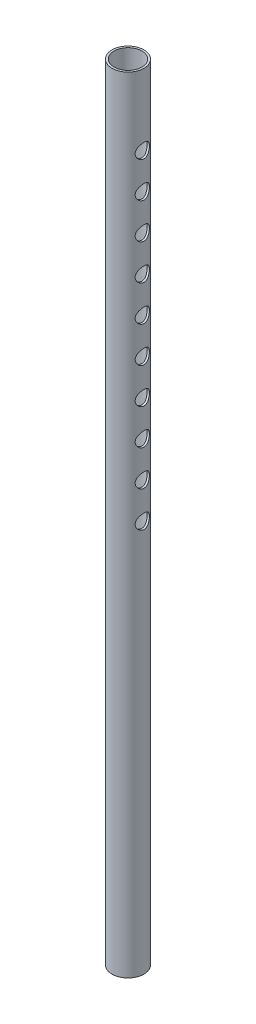
SolidWorks part; units mm, degrees
material "1060 Alloy"
ref_plane "Спереди" through (0, 0, 0) normal (0, 0, 1) x (1, 0, 0)
ref_plane "Сверху" through (0, 0, 0) normal (0, 1, 0) x (1, 0, 0)
ref_plane "Справа" through (0, 0, 0) normal (1, 0, 0) x (0, 0, -1)
sketch "Эскиз1" plane through (0, 0, 0) normal (0, 0, 1) x (1, 0, 0)
  line L0 (0, 0) -> (0, -550)
  dimension "D1" = 550
sketch "Эскиз2" plane through (0, 0, 0) normal (0, 1, 0) x (1, 0, 0)
  circle A0 centre (0, 0) radius 11.2
  circle A1 centre (0, 0) radius 9.775
  dimension "D1" = 22.4
  dimension "D2" = 19.55
sweep "По траектории1" add profiles "Эскиз2" path "Эскиз1"
sketch "Эскиз3" plane through (0, 0, 0) normal (1, 0, 0) x (0, 0, -1)
  line L0 (0, 0) -> (0, -343.1833) construction
  circle A0 centre (0, -50) radius 5
  circle A1 centre (0, -75) radius 5
  circle A2 centre (0, -100) radius 5
  circle A3 centre (0, -125) radius 5
  circle A4 centre (0, -150) radius 5
  circle A5 centre (0, -175) radius 5
  circle A6 centre (0, -200) radius 5
  circle A7 centre (0, -225) radius 5
  circle A8 centre (0, -250) radius 5
  circle A9 centre (0, -275) radius 5
  dimension "D1" = 10
  dimension "D2" = 25
  dimension "D3" = 25
  dimension "D4" = 25
  dimension "D5" = 25
  dimension "D6" = 25
  dimension "D7" = 25
  dimension "D8" = 25
  dimension "D9" = 25
  dimension "D10" = 50
  dimension "D11" = 25
extrude "Вырез-Вытянуть1" cut sketch "Эскиз3" against normal through all and the other way through all
